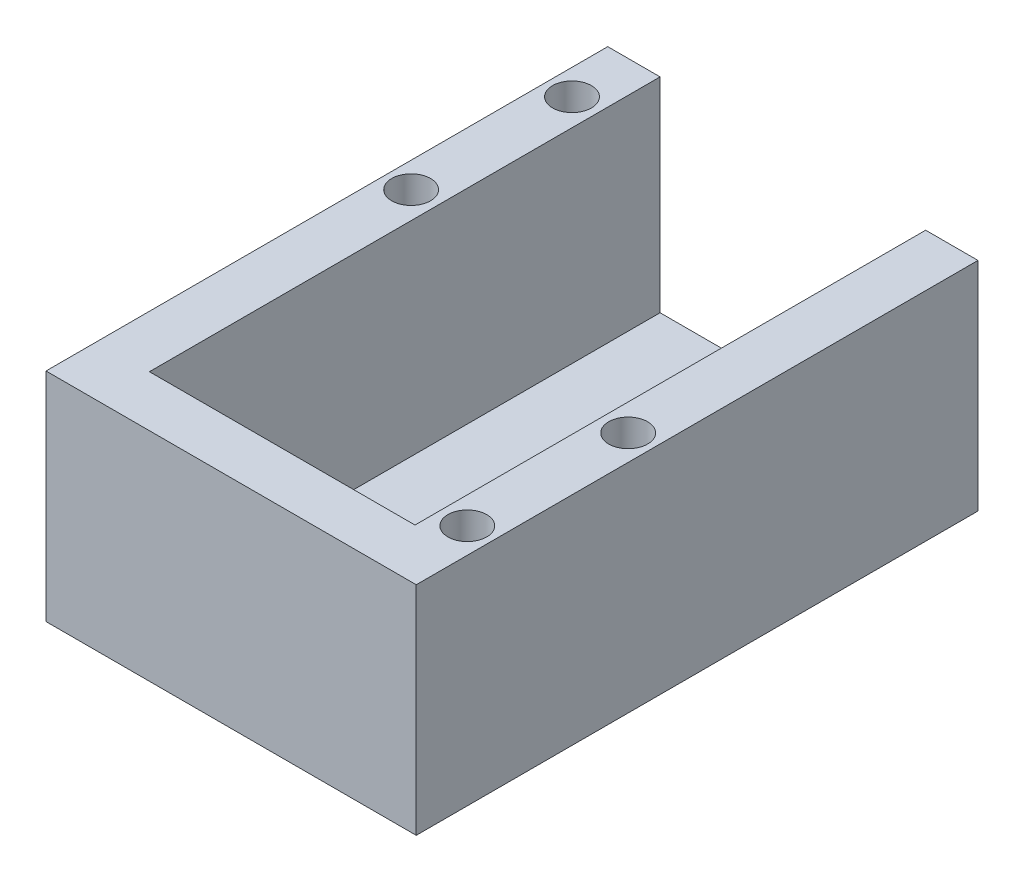
SolidWorks part; units mm, degrees
ref_plane "Front Plane" through (0, 0, 0) normal (0, 0, 1) x (1, 0, 0)
ref_plane "Top Plane" through (0, 0, 0) normal (0, 1, 0) x (1, 0, 0)
ref_plane "Right Plane" through (0, 0, 0) normal (1, 0, 0) x (0, 0, -1)
sketch "Sketch1" plane through (0, 0, 0) normal (0, 1, 0) x (1, 0, 0)
  line L1 (18.415, 0) -> (18.415, 55.88)
  line L3 (-18.415, 0) -> (-18.415, 55.88)
  line L4 (-18.415, 55.88) -> (18.415, 55.88)
  line L5 (-18.415, 0) -> (18.415, 0)
  point P0 (0, 0)
  dimension "D1" = 36.83
  dimension "D2" = 55.88
extrude "Boss-Extrude1" add sketch "Sketch1" along normal blind 21.59
sketch "Sketch3" plane through (0, 0, -55.88) normal (0, 0, -1) x (-1, 0, 0)
  line L0 (0, 21.59) -> (13.208, 21.59) construction
  line L1 (-18.415, 21.59) -> (18.415, 21.59) construction
  line L2 (0, 21.59) -> (-13.208, 21.59) construction
  line L4 (-13.208, 21.59) -> (13.208, 21.59)
  line L5 (-13.208, 21.59) -> (-13.208, 1.27)
  line L6 (-13.208, 1.27) -> (13.208, 1.27)
  line L7 (13.208, 21.59) -> (13.208, 1.27)
  dimension "D1" = 13.208
  dimension "D2" = 13.208
  dimension "D3" = 20.32
extrude "Cut-Extrude1" cut sketch "Sketch3" against normal blind 50.8
sketch "Sketch4" plane through (0, 21.59, 0) normal (0, 1, 0) x (1, 0, 0)
  line L0 (0, 5.08) -> (15.875, 5.08) construction
  line L1 (13.208, 5.08) -> (-13.208, 5.08) construction
  line L2 (15.875, 5.08) -> (15.875, 7.62) construction
  line L3 (15.875, 7.62) -> (15.875, 23.622) construction
  line L4 (15.875, 23.622) -> (15.875, 33.782) construction
  line L5 (15.875, 33.782) -> (-15.875, 33.782) construction
  line L6 (-15.875, 33.782) -> (-15.875, 49.784) construction
  dimension "D1" = 15.875
  dimension "D2" = 2.54
  dimension "D3" = 16.002
  dimension "D4" = 10.16
  dimension "D5" = 31.75
  dimension "D6" = 16.002
hole_wizard "Ø1.0 mm Dowel Holes1" positions "Sketch5" profile "Sketch6" hole size "Ø1.0" standard "ANSI Metric"
sketch "Sketch5" plane through (0, 21.59, 0) normal (0, 1, 0) x (1, 0, 0)
  point P0 (15.875, 7.62)
  point P3 (15.875, 23.622)
  point P6 (-15.875, 33.782)
  point P9 (-15.875, 49.784)
sketch "Sketch6" plane through (15.875, 21.59, -7.62) normal (1, 0, 0) x (0, 0, 1)
  line L0 (0, 0) -> (0, 6.2399)
  line L1 (0, 6.2399) -> (1.9304, 5.08)
  line L2 (1.9304, 5.08) -> (1.9304, 0)
  line L5 (1.9304, 0) -> (0, 0)
  line L10 (0, 6.2399) -> (-1.9304, 5.08) construction
  line L11 (0, -6.35) -> (0, 107.95) construction
  dimension "Hole Dia." = 3.8608
  dimension "Hole Depth" = 5.08
  dimension "Drill Angle" = 118
